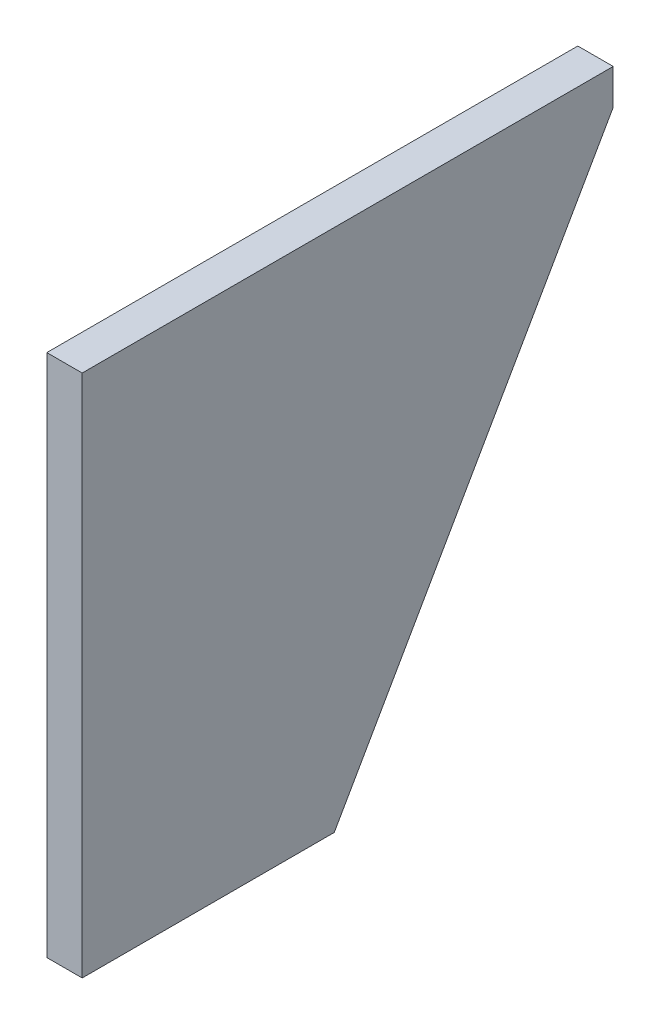
SolidWorks part; units mm, degrees
ref_plane "Alzado" through (0, 0, 0) normal (0, 0, 1) x (1, 0, 0)
ref_plane "Planta" through (0, 0, 0) normal (0, 1, 0) x (1, 0, 0)
ref_plane "Vista lateral" through (0, 0, 0) normal (1, 0, 0) x (0, 0, -1)
ref_plane "Plano1" through (-192.7541, 0, 0) normal (-1, 0, 0) x (0, 0, 1)
sketch "Croquis2" plane through (-192.7541, 0, 0) normal (-1, 0, 0) x (0, 0, 1)
  line L0 (334.8472, 111.3533) -> (334.8472, -258.6467)
  line L1 (334.8472, -258.6467) -> (156.8472, -258.6467)
  line L2 (156.8472, -258.6467) -> (-40.1528, 86.3533)
  line L3 (-40.1528, 86.3533) -> (-40.1528, 111.3533)
  line L4 (-40.1528, 111.3533) -> (334.8472, 111.3533)
extrude "Saliente-Extruir1" add sketch "Croquis2" against normal blind 20 and the other way blind 5
